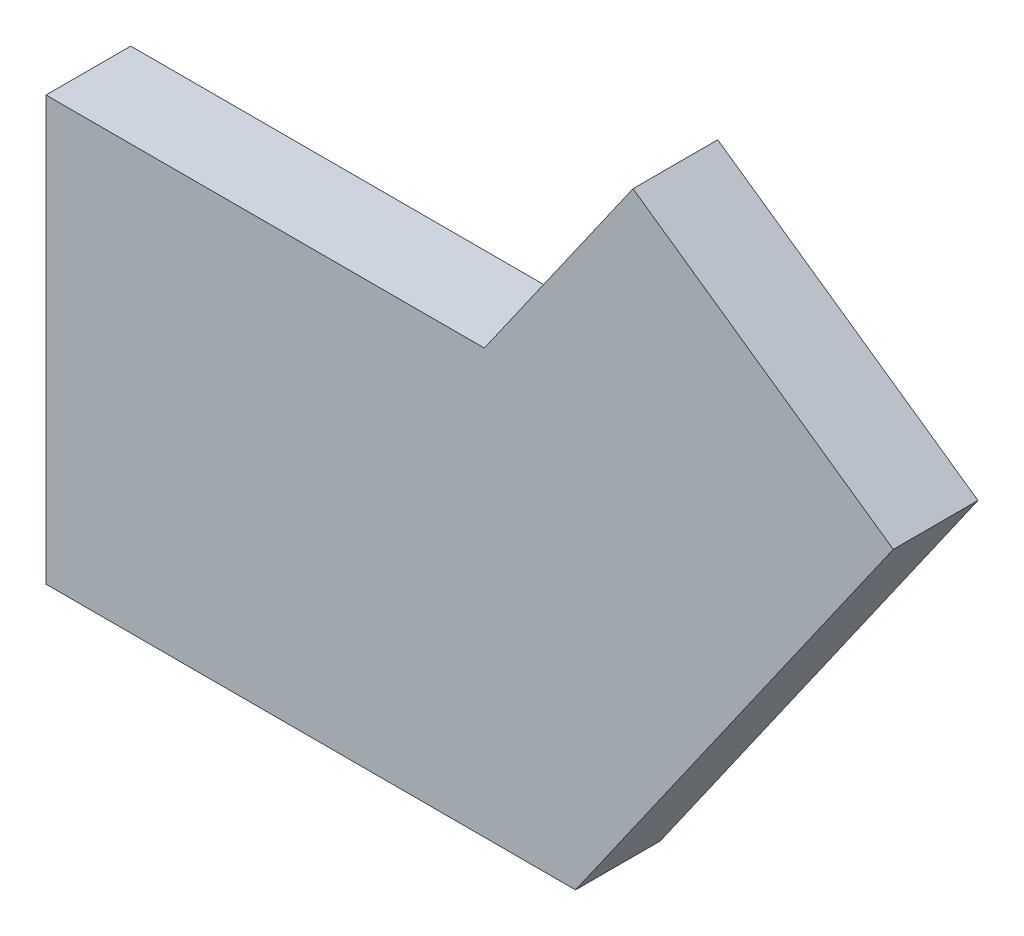
SolidWorks part; units mm, degrees
ref_plane "Front Plane" through (0, 0, 0) normal (0, 0, 1) x (1, 0, 0)
ref_plane "Top Plane" through (0, 0, 0) normal (0, 1, 0) x (1, 0, 0)
ref_plane "Right Plane" through (0, 0, 0) normal (1, 0, 0) x (0, 0, -1)
sketch "Sketch1" plane through (0, 0, 0) normal (0, 0, 1) x (1, 0, 0)
  line L0 (0, 0) -> (-125, 0)
  line L1 (-125, 0) -> (-125, 100)
  line L2 (-125, 100) -> (-21.5373, 100)
  line L3 (0, 0) -> (75, 107.1111)
  line L4 (75, 107.1111) -> (13.5636, 150.1293)
  line L5 (13.5636, 150.1293) -> (-21.5373, 100)
  dimension "D1" = 125
  dimension "D2" = 200
  dimension "D3" = 125
  dimension "D4" = 100
  dimension "D5" = 75
extrude "Boss-Extrude1" add sketch "Sketch1" along normal blind 20
